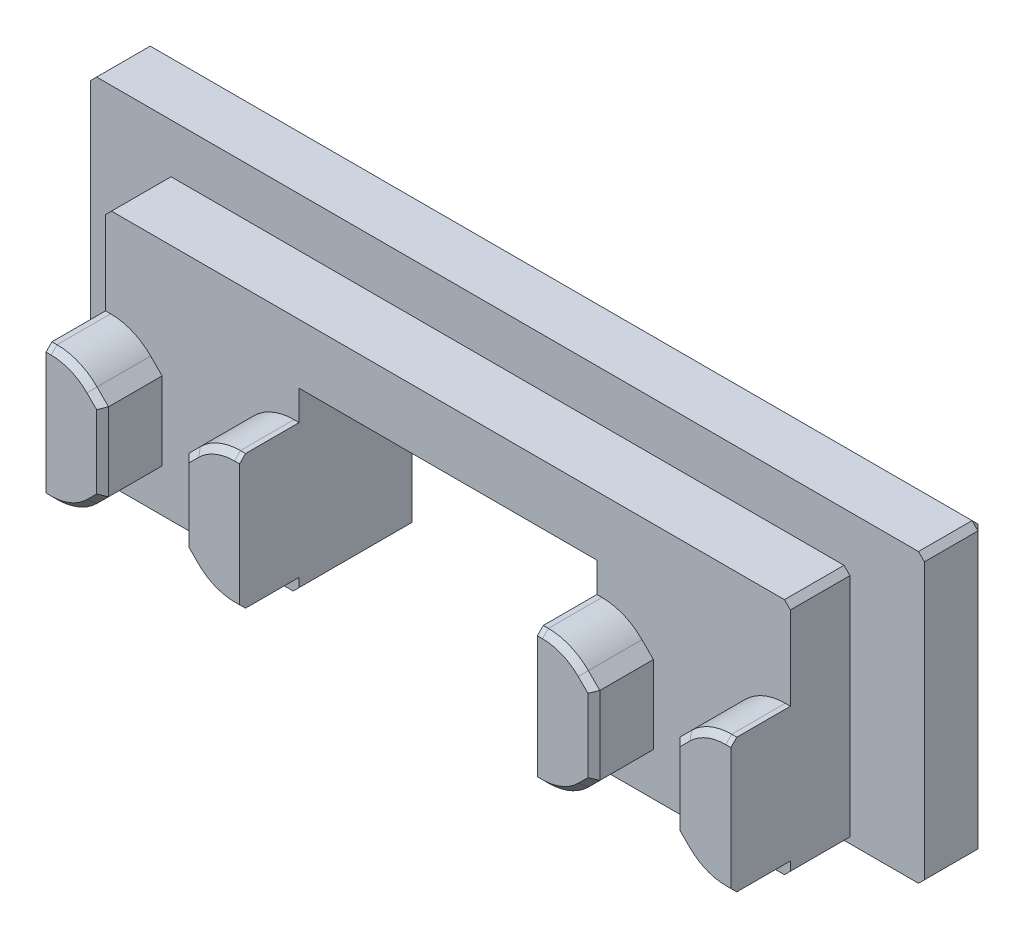
SolidWorks part; units mm, degrees
ref_plane "Front" through (0, 0, 0) normal (0, 0, 1) x (1, 0, 0)
ref_plane "Top" through (0, 0, 0) normal (0, 1, 0) x (1, 0, 0)
ref_plane "Right" through (0, 0, 0) normal (1, 0, 0) x (0, 0, -1)
sketch "Sketch1" plane through (0, 0, 0) normal (0, 0, 1) x (1, 0, 0)
  line L0 (-11.5, 4) -> (11.5, 4)
  line L5 (11.5, 4) -> (11.5, -4)
  line L6 (11.5, -4) -> (5, -4)
  line L7 (5, -4) -> (5, 2)
  line L8 (5, 2) -> (-5, 2)
  line L9 (-5, 2) -> (-5, -4)
  line L10 (-5, -4) -> (-11.5, -4)
  line L11 (-11.5, -4) -> (-11.5, 4)
  line L12 (5, -4) -> (11.5, -4) construction
  line L13 (11.3, 4) -> (-11.3, 4) construction
extrude "Boss-Extrude1" add sketch "Sketch1" against normal blind 2
sketch "Sketch2" plane through (0, 0, 0) normal (0, 0, 1) x (1, 0, 0)
  line L48 (11.5, 1) -> (11.5, -3.5)
  line L50 (11.5, -4) -> (11.5, 4) construction
  line L287 (13.9, -2.5586) -> (13.9, 0.0586)
  line L288 (13.9, 0.0586) -> (13.5151, 0.4435)
  line L289 (12.1716, 1) -> (11.3284, 1)
  line L290 (9.9849, 0.4435) -> (9.6, 0.0586)
  line L291 (9.6, 0.0586) -> (9.6, -2.5586)
  line L292 (9.6, -2.5586) -> (9.9849, -2.9435)
  line L293 (11.3284, -3.5) -> (12.1716, -3.5)
  line L294 (13.5151, -2.9435) -> (13.9, -2.5586)
  line L295 (13.9, -2.5586) -> (13.9, 0.0586)
  line L296 (13.9, 0.0586) -> (13.5151, 0.4435)
  line L297 (12.1716, 1) -> (11.3284, 1)
  line L298 (9.9849, 0.4435) -> (9.6, 0.0586)
  line L299 (9.6, 0.0586) -> (9.6, -2.5586)
  line L300 (9.6, -2.5586) -> (9.9849, -2.9435)
  line L301 (11.3284, -3.5) -> (12.1716, -3.5)
  line L302 (13.5151, -2.9435) -> (13.9, -2.5586)
  arc A143 (13.5151, 0.4435) -> (12.1716, 1) centre (12.1716, -0.9) ccw
  arc A144 (11.3284, 1) -> (9.9849, 0.4435) centre (11.3284, -0.9) ccw
  arc A145 (9.9849, -2.9435) -> (11.3284, -3.5) centre (11.3284, -1.6) ccw
  arc A146 (12.1716, -3.5) -> (13.5151, -2.9435) centre (12.1716, -1.6) ccw
  arc A147 (13.5151, 0.4435) -> (12.1716, 1) centre (12.1716, -0.9) ccw
  arc A148 (11.3284, 1) -> (9.9849, 0.4435) centre (11.3284, -0.9) ccw
  arc A149 (9.9849, -2.9435) -> (11.3284, -3.5) centre (11.3284, -1.6) ccw
  arc A150 (12.1716, -3.5) -> (13.5151, -2.9435) centre (12.1716, -1.6) ccw
  dimension "D1" = 0.1
extrude "Boss-Extrude2" add sketch "Sketch2" along normal blind 2
ref_plane "Plane1" through (8.25, 0, 0) normal (1, 0, 0) x (0, 0, -1)
mirror "Mirror1" about plane through (8.25, 0, 0) normal (1, 0, 0) of "Boss-Extrude2"
mirror "Mirror2" about plane through (0, 0, 0) normal (1, 0, 0) of "Mirror1", "Boss-Extrude2"
chamfer "Deburs" [suppressed] distance 0.2 angle 45
sketch "Sketch4" plane through (0, 0, -2) normal (0, 0, -1) x (-1, 0, 0)
  line L0 (-11.5, 4) -> (-11.5, -4) construction
  line L1 (11.5, -4) -> (14, -4)
  line L4 (14, -4) -> (14, 5.65)
  line L5 (-11.5, -4) -> (-14, -4)
  line L8 (-14, -4) -> (-14, 5.65)
  line L9 (11.5, 4) -> (-11.5, 4) construction
  line L10 (11.5, -4) -> (11.5, 4) construction
  line L11 (5, -4) -> (11.5, -4) construction
  line L12 (5, 2) -> (5, -4) construction
  line L13 (-5, 2) -> (5, 2) construction
  line L14 (-5, -4) -> (-5, 2) construction
  line L15 (-11.5, -4) -> (-5, -4) construction
  line L16 (-11.5, 4) -> (-11.5, -4) construction
  line L17 (11.5, 4) -> (-11.5, 4) construction
  line L18 (11.5, -4) -> (11.5, 4) construction
  line L19 (5, -4) -> (11.5, -4)
  line L20 (5, 2) -> (5, -4)
  line L21 (-5, 2) -> (5, 2)
  line L22 (-5, -4) -> (-5, 2)
  line L23 (-11.5, -4) -> (-5, -4)
  line L24 (-14, 5.65) -> (14, 5.65)
  dimension "D1" = 9.65
  dimension "D2" = 28
extrude "Stopper" add sketch "Sketch4" along normal blind 2
chamfer "Stopper Deburs" distance 0.2 angle 45 46 edges at (11.5, 4, -1) (-11.5, 4, -1) (-11.5, -4, -1) (11.5, -4, -1) (-5, -1, -4) (0, 2, -4) (5, -1, -4) (5, -4, -2) (9.5, -4, -4) (-5, -4, -2) (-9.5, -4, -4) (-14, -4, -3) (-14, 0.825, -4) (-14, 5.65, -3) (0, 5.65, -4) (14, 5.65, -3) (14, 0.825, -4) (14, -4, -3) (11.4142, -3.5, 2) (11.4142, 1, 2) (10.6013, -3.3554, 2) (10.6013, 0.8554, 2) (9.7925, -2.751, 2) (9.6, -1.25, 2) (9.7925, 0.251, 2) (5.0858, 1, 2) (5.0858, -3.5, 2) (5.8987, 0.8554, 2) (5.8987, -3.3554, 2) (6.7075, 0.251, 2) (6.9, -1.25, 2) (6.7075, -2.751, 2) (-5.0858, 1, 2) (-5.0858, -3.5, 2) (-5.8987, 0.8554, 2) (-5.8987, -3.3554, 2) (-6.7075, 0.251, 2) (-6.9, -1.25, 2) (-6.7075, -2.751, 2) (-11.4142, 1, 2) (-11.4142, -3.5, 2) (-10.6013, 0.8554, 2) (-10.6013, -3.3554, 2) (-9.7925, 0.251, 2) (-9.7925, -2.751, 2) (-9.6, -1.25, 2)
